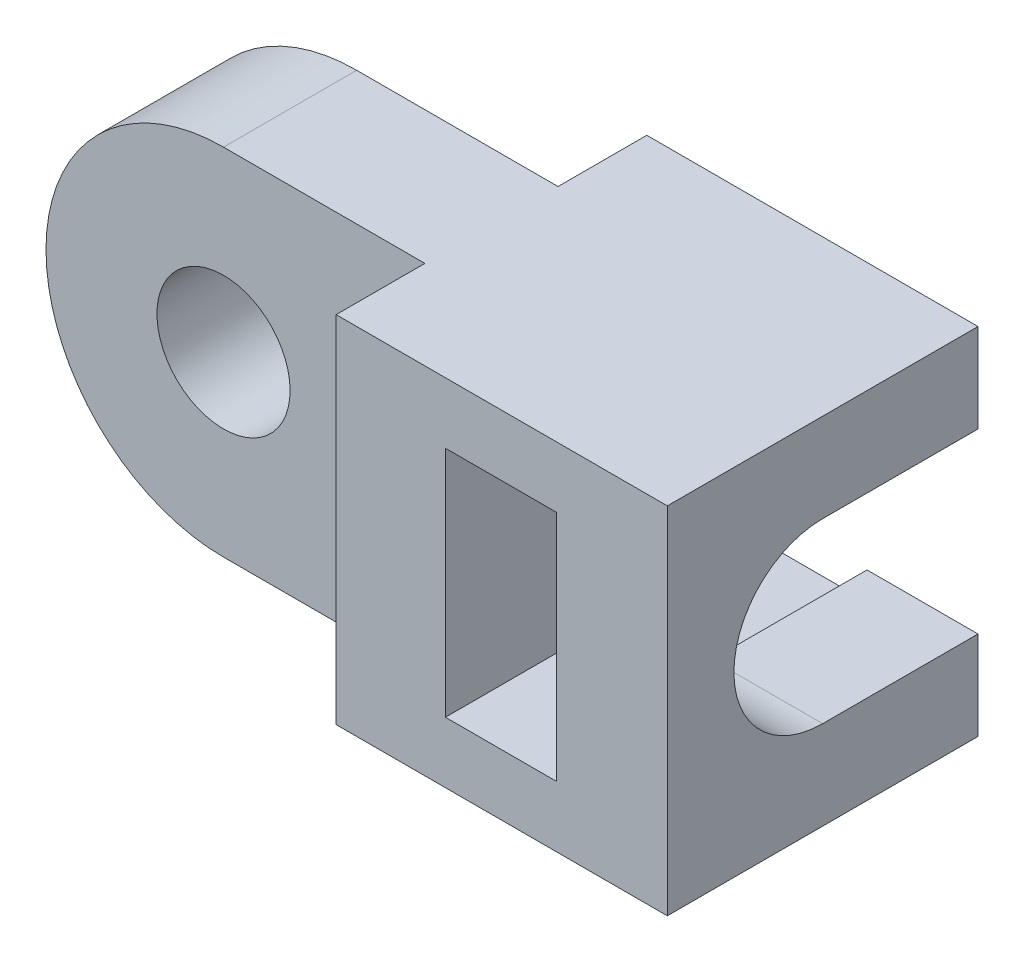
SolidWorks part; units mm, degrees
ref_plane "Спереди" through (0, 0, 0) normal (0, 0, 1) x (1, 0, 0)
ref_plane "Сверху" through (0, 0, 0) normal (0, 1, 0) x (1, 0, 0)
ref_plane "Справа" through (0, 0, 0) normal (1, 0, 0) x (0, 0, -1)
sketch "Sketch1" plane through (0, 0, 0) normal (0, 0, 1) x (1, 0, 0)
  line L0 (0, 0) -> (5.6788, 0) construction
  line L1 (0, 4) -> (12, 4)
  line L2 (0, -4) -> (12, -4)
  line L3 (12, 4) -> (12, -4)
  line L4 (12, -2) -> (12, 2)
  circle A0 centre (0, 0) radius 1.5
  circle A1 centre (0, 0) radius 4
  point P12 (12, 0)
  dimension "D1" = 3
  dimension "D2" = 8
  dimension "D3" = 4
  dimension "D4" = 4
  dimension "D5" = 12
  dimension "D6" = 4
extrude "Boss-Extrude1" add sketch "Sketch1" along normal mid plane 3
sketch "Sketch5" plane through (0, 0, 0) normal (0, 0, 1) x (1, 0, 0)
  line L0 (0, 4) -> (12, 4) construction
  line L1 (12, -4) -> (4.5369, -4)
  line L2 (12, -4) -> (12, 4)
  line L3 (12, 4) -> (4.5369, 4)
  line L4 (4.5369, -4) -> (4.5369, 4)
extrude "Boss-Extrude2" add sketch "Sketch5" along normal mid plane 7
sketch "Sketch2" plane through (0, 0, 1.5) normal (0, 0, 1) x (1, 0, 0)
  line L0 (12, 0) -> (8.25, 0) construction
  line L1 (12, 4) -> (12, -4) construction
  line L3 (7, 2.625) -> (9.5, 2.625)
  line L4 (7, 2.625) -> (7, -2.625)
  line L5 (7, -2.625) -> (9.5, -2.625)
  line L6 (9.5, 2.625) -> (9.5, -2.625)
  line L7 (7, 2.625) -> (9.5, -2.625) construction
  line L8 (7, -2.625) -> (9.5, 2.625) construction
  dimension "D1" = 2.5
  dimension "D2" = 5.25
  dimension "D3" = 2.5
extrude "Cut-Extrude1" cut sketch "Sketch2" against normal blind 6 and the other way blind 7
sketch "Sketch3" plane through (12, 0, 0) normal (1, 0, 0) x (0, 0, -1)
  circle A0 centre (0, 0) radius 2
  dimension "D1" = 4
extrude "Cut-Extrude2" cut sketch "Sketch3" against normal blind 3
sketch "Sketch6" plane through (0, 0, -3.5) normal (0, 0, -1) x (-1, 0, 0)
  line L0 (0, 0) -> (-12, 0) construction
  line L1 (-12, -4) -> (-12, 4) construction
  line L2 (-9.5, 2.625) -> (-9.5, -2.625) construction
  line L3 (-14.5, -2) -> (-9.5, -2)
  line L4 (-14.5, -2) -> (-14.5, 2)
  line L5 (-14.5, 2) -> (-9.5, 2)
  line L6 (-9.5, -2) -> (-9.5, 2)
  line L7 (-14.5, -2) -> (-9.5, 2) construction
  line L8 (-14.5, 2) -> (-9.5, -2) construction
  dimension "D1" = 4
extrude "Cut-Extrude3" cut sketch "Sketch6" against normal blind 3.5
